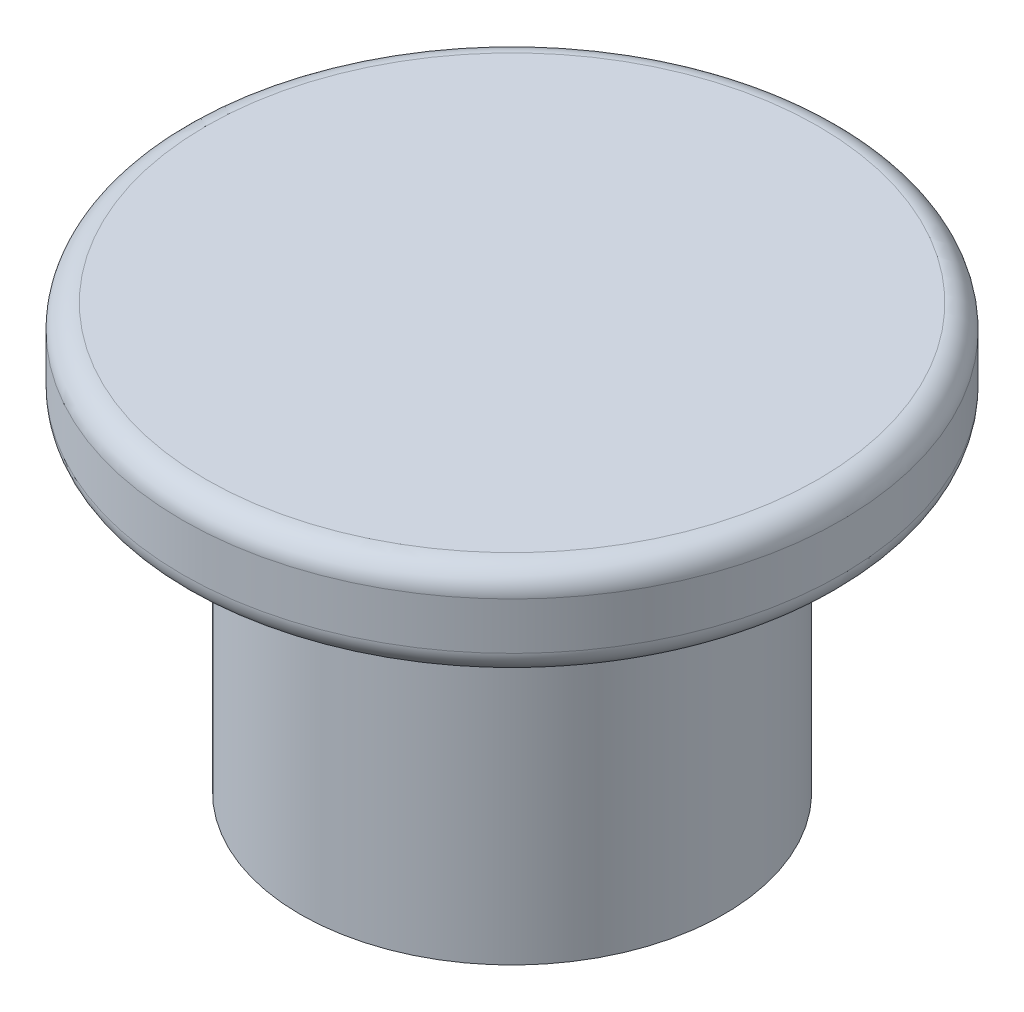
SolidWorks part; units mm, degrees
ref_plane "Front Plane" through (0, 0, 0) normal (0, 0, 1) x (1, 0, 0)
ref_plane "Top Plane" through (0, 0, 0) normal (0, 1, 0) x (1, 0, 0)
ref_plane "Right Plane" through (0, 0, 0) normal (1, 0, 0) x (0, 0, -1)
sketch "Sketch1" plane through (0, 0, 0) normal (0, 1, 0) x (1, 0, 0)
  circle A0 centre (0, 0) radius 3.5
  dimension "D1" = 7
extrude "Boss-Extrude1" add sketch "Sketch1" along normal blind 1
sketch "Sketch3" plane through (0, 0, 0) normal (0, -1, 0) x (1, 0, 0)
  circle A0 centre (0, 0) radius 2.25
  circle A1 centre (0, 0) radius 3.5 construction
  dimension "D1" = 4.5
  dimension "D2" = 1.25
extrude "Boss-Extrude3" add sketch "Sketch3" along normal blind 3.5
fillet "Fillet1" radius 0.25 2 edges at (0, 0, 3.5) (0, 1, 3.5)
hole_wizard "1/16 (0.07874016) Diameter Hole1" positions "Sketch8" profile "Sketch7" hole size "1/16" standard "ANSI Inch"
sketch "Sketch8" plane through (0, -3.5, 0) normal (0, -1, 0) x (-1, 0, 0)
  point P0 (0, 0)
sketch "Sketch7" plane through (0, -3.5, 0) normal (1, 0, 0) x (0, 0, -1)
  line L0 (0, 0) -> (0, 2.5)
  line L1 (0, 2.5) -> (1, 1.8991)
  line L2 (1, 1.8991) -> (1, 0)
  line L5 (1, 0) -> (0, 0)
  line L10 (0, 2.5) -> (-1, 1.8991) construction
  line L11 (0, -6.35) -> (0, 107.95) construction
  dimension "Hole Dia." = 2
  dimension "Hole Depth" = 2.5
  dimension "Drill Angle" = 118
fillet "Fillet2" radius 0.15 1 edges at (0, -3.5, -1)
